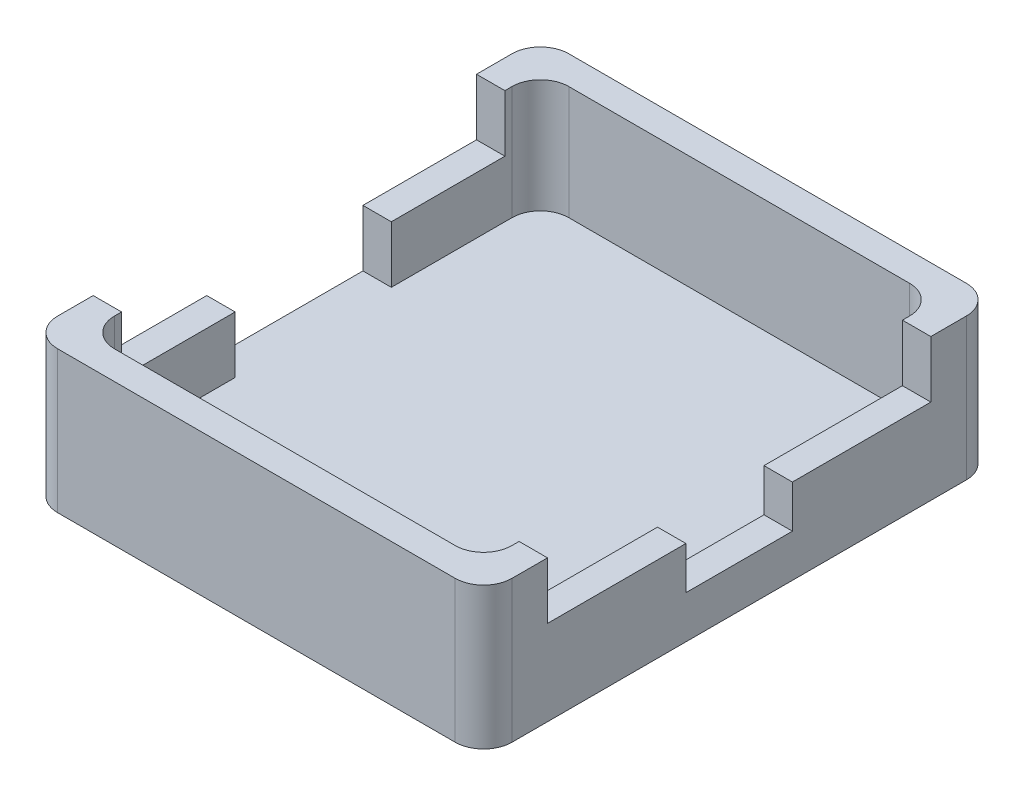
SolidWorks part; units mm, degrees
ref_plane "Front Plane" through (0, 0, 0) normal (0, 0, 1) x (1, 0, 0)
ref_plane "Top Plane" through (0, 0, 0) normal (0, 1, 0) x (1, 0, 0)
ref_plane "Right Plane" through (0, 0, 0) normal (1, 0, 0) x (0, 0, -1)
sketch "Sketch1" plane through (0, 0, 0) normal (0, 1, 0) x (1, 0, 0)
  line L0 (-16, 0) -> (16, 0) construction
  line L1 (-16, -18) -> (16, -18)
  line L2 (-16, -18) -> (-16, 18)
  line L3 (-16, 18) -> (16, 18)
  line L4 (16, -18) -> (16, 18)
  line L5 (-16, -18) -> (16, 18) construction
  line L6 (-16, 18) -> (16, -18) construction
  point P0 (0, 0)
  dimension "D1" = 32
  dimension "D2" = 36
extrude "Boss-Extrude1" add sketch "Sketch1" along normal blind 2
sketch "Sketch2" plane through (0, 2, 0) normal (0, 1, 0) x (1, 0, 0)
  line L1 (-16, 18) -> (-16, -18)
  line L20 (-16, -18) -> (16, -18)
  line L21 (-16, -18) -> (-16, 18)
  line L22 (-16, 18) -> (16, 18)
  line L23 (16, -18) -> (16, 18)
  line L24 (-16, -18) -> (16, 18) construction
  line L25 (-16, 18) -> (16, -18) construction
  line L26 (-14, -16) -> (14, -16)
  line L27 (-14, -16) -> (-14, 16)
  line L28 (-14, 16) -> (14, 16)
  line L29 (14, -16) -> (14, 16)
  line L30 (-14, -16) -> (14, 16) construction
  line L31 (-14, 16) -> (14, -16) construction
  point P0 (0, 0)
  point P9 (0, 0)
  line M13 (16, -18) -> (16, 18)
  line M14 (16, 18) -> (-16, 18)
  line M15 (-16, 18) -> (-16, -18)
  line M16 (-16, -18) -> (16, -18)
  dimension "D1" = 2
  dimension "D2" = 2
extrude "Boss-Extrude2" add sketch "Sketch2" along normal blind 8 contours L29 L26 L27 L28 M16 M13 M14 M15
sketch "Sketch3" plane through (-16, 0, 0) normal (-1, 0, 0) x (0, 0, 1)
  line L0 (0, 0) -> (0, 10) construction
  line L1 (-18, 0) -> (18, 0) construction
  line L2 (-18, 10) -> (18, 10) construction
  line L3 (-13.5, 10) -> (-13.5, 6)
  line L4 (-13.5, 6) -> (-5.5, 6)
  line L5 (-5.5, 6) -> (-5.5, 2)
  line L6 (-5.5, 2) -> (5.5, 2)
  line L7 (-18, 10) -> (-18, 0) construction
  line L8 (5.5, 6) -> (5.5, 2)
  line L9 (13.5, 6) -> (5.5, 6)
  line L10 (13.5, 10) -> (13.5, 6)
  line L11 (-13.5, 10) -> (13.5, 10)
  point P14 (0, 2)
  dimension "D1" = 4
  dimension "D2" = 4.5
  dimension "D3" = 5.5
  dimension "D4" = 2
extrude "Cut-Extrude1" cut sketch "Sketch3" against normal up to surface (2 mm away) up to face at (-14, 6, 0)
sketch "Sketch4" plane through (16, 0, 0) normal (1, 0, 0) x (0, 0, -1)
  line L0 (0, 0) -> (0, 10) construction
  line L1 (-18, 10) -> (18, 10) construction
  line L2 (-13.5, 10) -> (-13.5, 6)
  line L3 (-13.5, 6) -> (-3.75, 6)
  line L4 (-3.75, 6) -> (-3.75, 3)
  line L5 (-3.75, 3) -> (3.75, 3)
  line L6 (-18, 10) -> (-18, 0) construction
  line L7 (3.75, 6) -> (3.75, 3)
  line L8 (13.5, 6) -> (3.75, 6)
  line L9 (13.5, 10) -> (13.5, 6)
  line L10 (-13.5, 10) -> (13.5, 10)
  point P13 (0, 3)
  dimension "D1" = 4
  dimension "D2" = 4.5
  dimension "D3" = 7.5
  dimension "D4" = 7
extrude "Cut-Extrude2" cut sketch "Sketch4" against normal up to surface (2 mm away) up to face at (14, 6, 0)
fillet "Fillet1" radius 2 8 edges at (-14, 6, 16) (-14, 6, -16) (14, 6, -16) (14, 6, 16) (-16, 5, 18) (-16, 5, -18) (16, 5, -18) (16, 5, 18)
